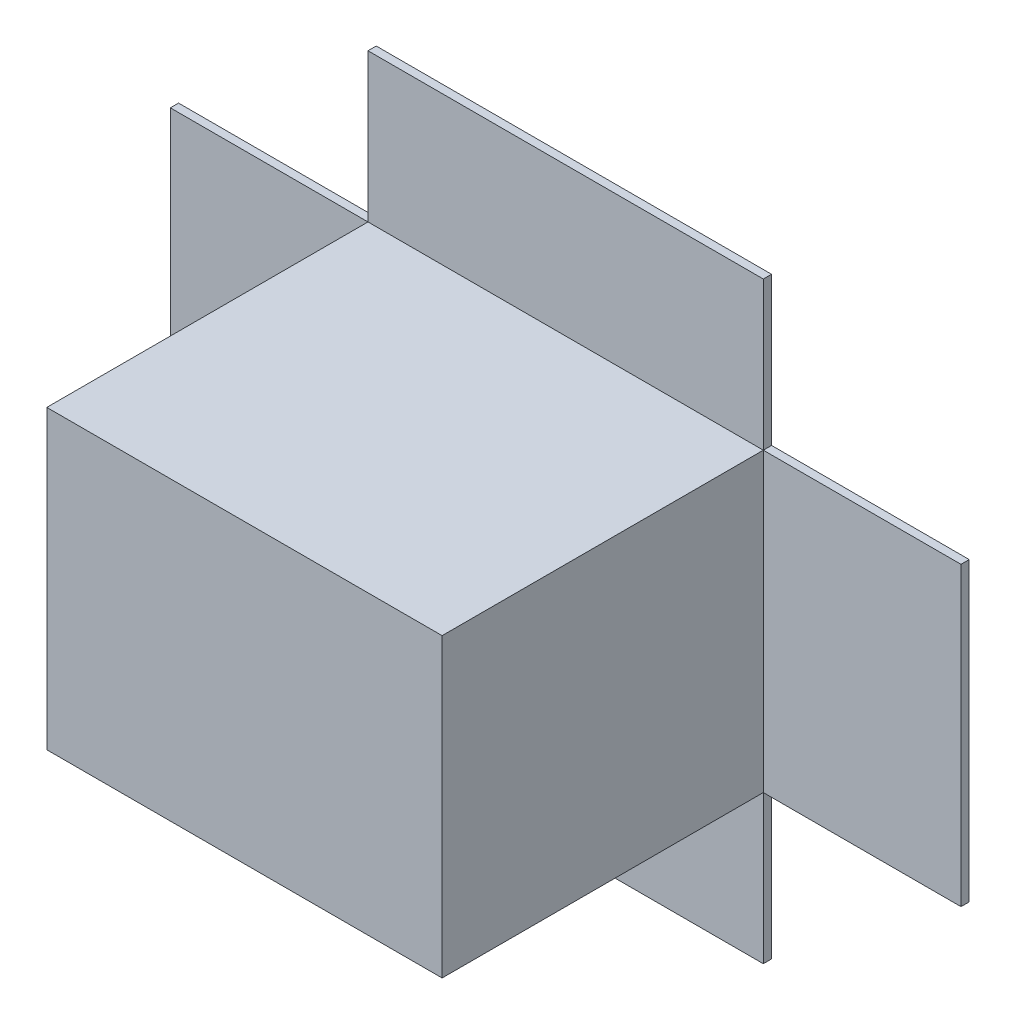
SolidWorks part; units mm, degrees
ref_plane "Alzado" through (0, 0, 0) normal (0, 0, 1) x (1, 0, 0)
ref_plane "Planta" through (0, 0, 0) normal (0, 1, 0) x (1, 0, 0)
ref_plane "Vista lateral" through (0, 0, 0) normal (1, 0, 0) x (0, 0, -1)
sketch "Croquis1" plane through (0, 0, 0) normal (0, 0, 1) x (1, 0, 0)
  line L1 (-60, -45) -> (60, -45)
  line L2 (-60, -45) -> (-60, 45)
  line L3 (-60, 45) -> (60, 45)
  line L4 (60, -45) -> (60, 45)
  line L5 (-60, -45) -> (60, 45) construction
  line L6 (-60, 45) -> (60, -45) construction
  point P0 (0, 0)
  dimension "D1" = 90
  dimension "D2" = 120
extrude "Saliente-Extruir1" add sketch "Croquis1" along normal blind 100
sketch "Croquis2" plane through (0, 0, 0) normal (0, 0, -1) x (-1, 0, 0)
  line L12 (-57.5, 42.5) -> (-57.5, -42.5)
  line L13 (-57.5, -42.5) -> (57.5, -42.5)
  line L14 (57.5, -42.5) -> (57.5, 42.5)
  line L15 (57.5, 42.5) -> (-57.5, 42.5)
  line L16 (-57.5, 42.5) -> (-57.5, -42.5)
  line L17 (-57.5, -42.5) -> (57.5, -42.5)
  line L18 (57.5, -42.5) -> (57.5, 42.5)
  line L19 (57.5, 42.5) -> (-57.5, 42.5)
  dimension "D1" = 2.5
extrude "Cortar-Extruir1" cut sketch "Croquis2" against normal blind 97.5
sketch "Croquis3" plane through (0, 0, 0) normal (0, 0, -1) x (-1, 0, 0)
  line L1 (-60, 45) -> (60, 45)
  line L2 (-60, 45) -> (-60, 90)
  line L3 (-60, 90) -> (60, 90)
  line L4 (60, 45) -> (60, 90)
  line L9 (-60, -45) -> (60, -45)
  line L10 (-60, -45) -> (-60, -90)
  line L11 (-60, -90) -> (60, -90)
  line L12 (60, -45) -> (60, -90)
  line L13 (-60, -45) -> (-120, -45)
  line L14 (-60, -45) -> (-60, 45)
  line L15 (-60, 45) -> (-120, 45)
  line L16 (-120, -45) -> (-120, 45)
  line L17 (60, 45) -> (120, 45)
  line L18 (60, 45) -> (60, -45)
  line L19 (60, -45) -> (120, -45)
  line L20 (120, 45) -> (120, -45)
  line L21 (-57.5, -42.5) -> (57.5, -42.5)
  line L22 (-57.5, -42.5) -> (-57.5, 42.5)
  line L23 (-57.5, 42.5) -> (57.5, 42.5)
  line L24 (57.5, -42.5) -> (57.5, 42.5)
  line L25 (-57.5, -42.5) -> (57.5, 42.5) construction
  line L26 (-57.5, 42.5) -> (57.5, -42.5) construction
  point P7 (0, 0)
  point P21 (0, 0)
  point P22 (0, 0)
  point P23 (-61.6139, -45)
  point P24 (0, 0)
  line M22 (-57.5, 42.5) -> (57.5, 42.5)
  line M23 (57.5, 42.5) -> (57.5, -42.5)
  line M24 (57.5, -42.5) -> (-57.5, -42.5)
  line M25 (-57.5, -42.5) -> (-57.5, 42.5)
  line M26 (-60, 45) -> (-60, -45)
  line M27 (-60, -45) -> (60, -45)
  line M28 (60, -45) -> (60, 45)
  line M29 (60, 45) -> (-60, 45)
  dimension "D1" = 60
  dimension "D2" = 60
  dimension "D3" = 45
  dimension "D4" = 45
extrude "Saliente-Extruir2" add sketch "Croquis3" against normal blind 2.5 contours L16 L13 L15 M26 | L4 L3 L2 M29 | M29 M26 M27 M28 M25 M22 M23 M24 | L20 L17 L19 M28 | L12 L10 L11 M27
